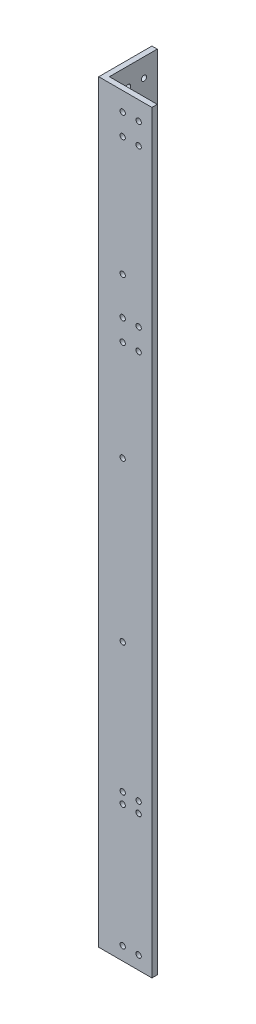
SolidWorks part; units mm, degrees
ref_plane "Front Plane" through (0, 0, 0) normal (0, 0, 1) x (1, 0, 0)
ref_plane "Top Plane" through (0, 0, 0) normal (0, 1, 0) x (1, 0, 0)
ref_plane "Right Plane" through (0, 0, 0) normal (1, 0, 0) x (0, 0, -1)
sketch "Sketch2" plane through (0, 0, 0) normal (0, 1, 0) x (1, 0, 0)
  line L0 (0, 31.75) -> (3.175, 31.75)
  line L1 (3.175, 31.75) -> (3.175, 3.175)
  line L2 (3.175, 3.175) -> (31.75, 3.175)
  line L3 (31.75, 3.175) -> (31.75, 0)
  line L4 (31.75, 0) -> (0, 0)
  line L5 (0, 0) -> (0, 31.75)
  point P9 (1.5875, 31.75)
  point P10 (31.75, 1.5875)
  dimension "D4" = 3.175
  dimension "D1" = 31.75
  dimension "D2" = 31.75
  dimension "D3" = 3.175
extrude "Boss-Extrude1" add sketch "Sketch2" along normal blind 450
sketch "RightSideHoles-Sketch3" plane through (0, 0, 0) normal (0, 0, 1) x (1, 0, 0)
  line L0 (0, 0) -> (31.75, 0) construction
  line L3 (0, 450) -> (0, 0) construction
  circle A0 centre (14.2875, 81.1125) radius 1.5875
  circle A1 centre (23.8125, 81.1125) radius 1.5875
  circle A2 centre (14.2875, 87.4625) radius 1.5875
  circle A3 centre (23.8125, 87.4625) radius 1.5875
  circle A4 centre (14.2875, 438.8875) radius 1.5875
  circle A5 centre (14.2875, 426.1875) radius 1.5875
  circle A6 centre (23.8125, 438.8875) radius 1.5875
  circle A7 centre (23.8125, 426.1875) radius 1.5875
  circle A8 centre (14.2875, 332.6026) radius 1.5875
  circle A9 centre (23.8125, 332.6026) radius 1.5875
  circle A10 centre (14.2875, 319.9026) radius 1.5875
  circle A11 centre (23.8125, 319.9026) radius 1.5875
  circle A12 centre (14.2875, 7.9375) radius 1.5875
  circle A13 centre (23.8125, 7.9375) radius 1.5875
  circle A14 centre (14.2875, 165) radius 1.5875
  circle A15 centre (14.2875, 260) radius 1.5875
  circle A16 centre (14.2875, 355) radius 1.5875
  dimension "D4" = 3.175
  dimension "D1" = 81.1125
  dimension "D2" = 14.2875
  dimension "D8" = 11.1125
  dimension "D12" = 7.9375
  dimension "D5" = 6.35
  dimension "D7" = 12.7
  dimension "D9" = 12.7
  dimension "D3" = 9.525
  dimension "D10" = 332.6026
  dimension "D11" = 165
  dimension "D13" = 95
  dimension "D14" = 95
sketch "FrontSideHoles-Sketch4" plane through (0, 0, 0) normal (-1, 0, 0) x (0, 0, 1)
  line L0 (-31.75, 450) -> (0, 450) construction
  line L1 (0, 450) -> (0, 0) construction
  line L3 (-31.75, 0) -> (0, 0) construction
  circle A0 centre (-23.8125, 81.1125) radius 1.5875
  circle A1 centre (-14.2875, 81.1125) radius 1.5875
  circle A2 centre (-23.8125, 87.4625) radius 1.5875
  circle A3 centre (-14.2875, 87.4625) radius 1.5875
  circle A4 centre (-23.8125, 438.8875) radius 1.5875
  circle A5 centre (-14.2875, 438.8875) radius 1.5875
  circle A6 centre (-23.8125, 426.1875) radius 1.5875
  circle A7 centre (-14.2875, 426.1875) radius 1.5875
  circle A8 centre (-14.2875, 338.1776) radius 1.5875
  circle A9 centre (-14.2875, 319.6526) radius 1.5875
  circle A10 centre (-14.2875, 165) radius 1.5875
  circle A11 centre (-14.2875, 260) radius 1.5875
  circle A12 centre (-14.2875, 355) radius 1.5875
  dimension "D4" = 3.175
  dimension "D2" = 14.2875
  dimension "D5" = 6.35
  dimension "D7" = 12.7
  dimension "D13" = 95
  dimension "D14" = 95
  dimension "D3" = 81.1125
  dimension "D6" = 11.1125
  dimension "D9" = 18.525
  dimension "D10" = 14.2875
  dimension "D11" = 9.525
  dimension "D8" = 319.6526
  dimension "D12" = 165
extrude "RightSideHoles-Cut-Extrude1" cut sketch "RightSideHoles-Sketch3" against normal blind 3.175
extrude "FrontSideHoles-Cut-Extrude2" cut sketch "FrontSideHoles-Sketch4" against normal blind 3.175
equation "\"RailThickness\"= .125in'Spec"
equation "\"VSWidth\"= 1.25in'Spec"
equation "\"VSHeight\"= 1.25in'Spec"
equation "\"VSLength\"= 450mm"
equation "\"HoleOffsetFromEdge\"= \"RailThickness\" * 2.5"
equation "\"HoleOffsetFromSide\"= \"RailThickness\" * 3.5"
equation "\"LegHeight\"= 70mm'Space needed for PSU/Stepper/Electronics"
equation "\"VSBottomSideRailHoleY1FromBottomOfLowerRail\"= \"V1 BottomOfLowerRail\" + \"HoleOffsetFromSide\"'Equals 70.1125"
equation "\"VSSideRailHoleX1FromSide\"= \"HoleOffsetFromSide\" + \"RailThickness\""
equation "\"FasteningHoleDiameter\"= .125in"
equation "\"VSBottomSideRailHoleY2FromY1\"= \"LowerRailHeight\" - \"HoleOffsetFromSide\" - \"HoleOffsetFromEdge\"'Equals 6.35"
equation "\"VSTopSideRailHoleY1FromEdge\"= \"HoleOffsetFromEdge\" + \"RailThickness\""
equation "\"D4@RightSideHoles-Sketch3\" = \"FasteningHoleDiameter\""
equation "\"D1@RightSideHoles-Sketch3\" = \"VSBottomSideRailHoleY1FromBottomOfLowerRail\""
equation "\"D2@RightSideHoles-Sketch3\" = \"VSSideRailHoleX1FromSide\""
equation "\"D1@Boss-Extrude1\"=\"VSLength\""
equation "\"D4@FrontSideHoles-Sketch4\" = \"FasteningHoleDiameter\""
equation "\"D3@FrontSideHoles-Sketch4\" = \"VSBottomSideRailHoleY1FromBottomOfLowerRail\""
equation "\"D2@FrontSideHoles-Sketch4\" = \"VSSideRailHoleX1FromSide\""
equation "\"D8@RightSideHoles-Sketch3\" = \"VSTopSideRailHoleY1FromEdge\""
equation "\"D6@FrontSideHoles-Sketch4\" = \"VSTopSideRailHoleY1FromEdge\""
equation "\"VSMidSideRailHoleY1FromV8TopOfMidSideRail\"= \"V8 ToTopOfMidSideRail\" - \"HoleOffsetFromEdge\"'Equals 308.2875"
equation "\"LowerRailHeight\"= 1.00in"
equation "\"D2@Sketch2\"=\"VSWidth\""
equation "\"D1@Sketch2\"=\"VSHeight\""
equation "\"TopRailHeight\"= 1.25in"
equation "\"MidSideRailHeight\"= 1.25in"
equation "\"D12@RightSideHoles-Sketch3\"=\"HoleOffsetFromEdge\""
equation "\"D5@RightSideHoles-Sketch3\"=\"VSBottomSideRailHoleY2FromY1\""
equation "\"D5@FrontSideHoles-Sketch4\"=\"VSBottomSideRailHoleY2FromY1\""
equation "\"VSMidSideRailHoleY2FromY1\"= \"MidSideRailHeight\" - \"HoleOffsetFromSide\" - \"HoleOffsetFromEdge\"'Equals 12.7"
equation "\"D7@RightSideHoles-Sketch3\"=\"VSMidSideRailHoleY2FromY1\""
equation "\"VSTopSideRailHoleY2FromY1\"= \"TopRailHeight\" - \"VSTopSideRailHoleY1FromEdge\" - \"HoleOffsetFromEdge\"'Equals 12.7"
equation "\"D9@RightSideHoles-Sketch3\"=\"VSTopSideRailHoleY2FromY1\""
equation "\"D7@FrontSideHoles-Sketch4\"=\"VSTopSideRailHoleY2FromY1\""
equation "\"VSSideRailHoleX2FromX1\"= \"VSWidth\" - \"VSSideRailHoleX1FromSide\" - \"HoleOffsetFromEdge\""
equation "\"D3@RightSideHoles-Sketch3\"=\"VSSideRailHoleX2FromX1\""
equation "\"D11@FrontSideHoles-Sketch4\"=\"VSSideRailHoleX2FromX1\""
equation "\"1mmSpacer\"= 1mm"
equation "\"20TGT2PulleyWidth\"= 8.7mm'The STL of the Pulley in the diagram is a bit larger"
equation "\"BeltTensionerUpperLowerWallThickness\"= 7mm"
equation "\"BeltTensionerInnerHeight\"= \"20TGT2PulleyWidth\" * 2 + \"1mmSpacer\" * 3"
equation "\"BeltTensionerHeight\"= \"BeltTensionerInnerHeight\" + \"BeltTensionerUpperLowerWallThickness\" * 2"
equation "\"D9@FrontSideHoles-Sketch4\"=\"VSBeltTensionerHoleY2FromY1\""
equation "\"VSBeltTensionerHoleY1FromBottom\"= \"V9 FromBottomGantryPulleyToBottomOfBeltTensioner\" + \"HoleOffsetFromEdge\""
equation "\"VSBeltTensionerHoleY2FromY1\"= \"BeltTensionerHeight\" - \"HoleOffsetFromEdge\" * 2"
equation "\"V1 BottomOfLowerRail\"= \"LegHeight\""
equation "\"StepperShaftLength\"= 24mm'Pulley will be attached to the end"
equation "\"ZAxisLeadScrewLength\"= 200mm"
equation "\"LM8UUHeight\"= 24mm'Spec"
equation "\"V2 ToBedAtTopOfZAxis\"= \"V1 BottomOfLowerRail\" + \"StepperShaftLength\" + \"ZAxisLeadScrewLength\" - \"LM8UUHeight\" / 2"
equation "\"HotEndToTopOfXAxisGB\"= 63.315144mm'Measured from the100.Should be 63.315144"
equation "\"TopOfGBToBottomOfLinearRail\"= \"LinearGBWidth\" / 2 + \"LinearRailWidth\" / 2"
equation "\"LinearGBWidth\"= 27mm'Spec"
equation "\"V5 ToBottomOfXAxisLinearRail\"= \"V4 ToTopOfBuildPlate/HotEndTip\" + \"HotEndToTopOfXAxisGB\" - \"TopOfGBToBottomOfLinearRail\""
equation "\"LinearRailWidth\"= 12mm'Spec"
equation "\"V6 ToBottomOfGantryPulley\"= \"V5 ToBottomOfXAxisLinearRail\" - \"DistanceFromGABTopToLowerPulley\""
equation "\"GABUpperHeight\"= 6mm"
equation "\"GABMidWallHeight\"= 28mm'Must equal 28 or changes alignment"
equation "\"GABMidShortRiserHeight\"= \"GABMidWallHeight\" / 2 - \"20TGT2PulleyWidth\"'Equals 5.3"
equation "\"GABRiserBossOffset\"= 0.8mm'Aligns Pulleys"
equation "\"DistanceFromGABTopToLowerPulley\"= \"GABUpperHeight\" + \"GABMidWallHeight\" - \"GABMidShortRiserHeight\" + \"GABRiserBossOffset\" / 2"
equation "\"V7 ToTopOfMidBackRail\"= \"V6 ToBottomOfGantryPulley\" + \"StepperShaftLength\""
equation "\"D10@RightSideHoles-Sketch3\"=\"VSMidSideRailHoleY1FromV8TopOfMidSideRail\""
equation "\"BedToBuildPlateStandoffLength\"= 15mm"
equation "\"BuildPlateHeight\"= 8mm'Spec"
equation "\"V4 ToTopOfBuildPlate/HotEndTip\"= \"V2 ToBedAtTopOfZAxis\" + \"BedToBuildPlateStandoffLength\" + \"BuildPlateHeight\""
equation "\"D8@FrontSideHoles-Sketch4\"=\"VSBeltTensionerHoleY1FromBottom\""
equation "\"V8 ToTopOfMidSideRail\"= \"V7 ToTopOfMidBackRail\" - \"RailThickness\""
equation "\"V9 FromBottomGantryPulleyToBottomOfBeltTensioner\"= \"V6 ToBottomOfGantryPulley\" - \"BeltTensionerUpperLowerWallThickness\" - \"1mmSpacer\""
equation "\"BeltTensionerMountingHoleOffsetFromEdge\"= \"HoleOffsetFromEdge\""
equation "\"VSBeltTensionerXMountingHoleOffsetFromSide\"= \"BeltTensionerMountingHoleOffsetFromEdge\" + \"RailThickness\" * 2"
equation "\"D10@FrontSideHoles-Sketch4\"=\"VSBeltTensionerXMountingHoleOffsetFromSide\""
equation "\"VSEnclosureOffsets\"= ( \"VSLength\" - \"LegHeight\" ) / 4"
equation "\"D11@RightSideHoles-Sketch3\"=\"LegHeight\" + \"VSEnclosureOffsets\""
equation "\"D13@RightSideHoles-Sketch3\"=\"VSEnclosureOffsets\""
equation "\"D14@RightSideHoles-Sketch3\"=\"VSEnclosureOffsets\""
equation "\"D12@FrontSideHoles-Sketch4\"= \"LegHeight\" + \"VSEnclosureOffsets\""
equation "\"D13@FrontSideHoles-Sketch4\"=\"VSEnclosureOffsets\""
equation "\"D14@FrontSideHoles-Sketch4\"=\"VSEnclosureOffsets\""
